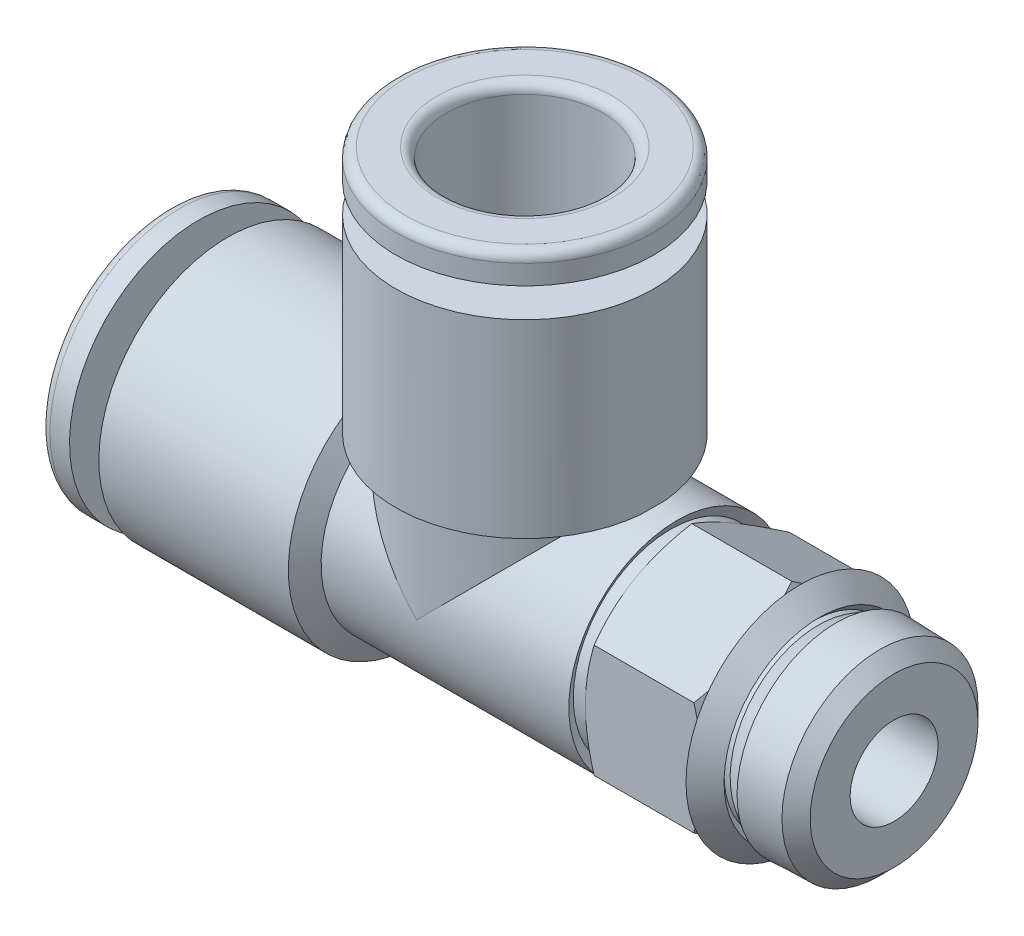
SolidWorks part; units mm, degrees
material "Nylon 101"
ref_plane "Front Plane" through (0, 0, 0) normal (0, 0, 1) x (1, 0, 0)
ref_plane "Top Plane" through (0, 0, 0) normal (0, 1, 0) x (1, 0, 0)
ref_plane "Right Plane" through (0, 0, 0) normal (1, 0, 0) x (0, 0, -1)
sketch "Sketch0" plane through (0, 0, 0) normal (0, 0, -1) x (-1, 0, 0)
  line L0 (0, 0) -> (-37.1, 0) construction
  line L1 (0, 6.6) -> (0, -6.6) construction
  line L2 (-14.2, 4) -> (-14.2, -4) construction
  line L3 (-32.3, 5.1435) -> (-32.3, -5.1435) construction
  line L4 (-18.55, 5) -> (-18.55, -5) construction
  line L5 (-37.1, 2.25) -> (-37.1, -2.25) construction
  line L6 (-18.2, 18.2) -> (-18.2, 0) construction
  line L7 (-32.3, 5) -> (-32.3, -5) construction
  line L8 (-18.2, 18.2) -> (-18.2, 4.001) construction
  point P3 (-14.2, 0)
  point P11 (-18.55, 0)
  point P16 (-32.3, 0)
  dimension "D3" = 14.199
sketch "Sketch1" plane through (0, 0, 0) normal (0, 0, -1) x (-1, 0, 0)
  line L0 (0, 6.1) -> (0, 4.5)
  line L1 (-0.5, 6.6) -> (-1.5, 6.6)
  line L2 (-1.5, 6.6) -> (-1.5, 4.475)
  line L3 (-1.5, 4.475) -> (-3, 4.475)
  line L4 (-3, 4.475) -> (-3, 6.6)
  line L5 (-3, 6.6) -> (-12.6989, 6.6)
  line L6 (-13.3123, 5.5375) -> (-18.2, 5.5375)
  line L7 (0, 0) -> (-37.1, 0) construction
  line L8 (-18.2, 0) -> (-14.2, 0)
  line L9 (-14.2, 4) -> (-14.2, 0)
  line L10 (0, 0) -> (-37.1, 0) construction
  line L11 (-14.2, 4) -> (-0.5, 4)
  line L12 (0, 6.6) -> (0, -6.6) construction
  line L13 (-18.2, 18.2) -> (-18.2, 0) construction
  line L15 (-18.2, 5.5375) -> (-18.2, 0)
  line L16 (-12.6989, 6.6) -> (-13.3123, 5.5375)
  line L17 (-13.3123, 5.5375) -> (-14.2, 4) construction
  line L18 (-3, 5.5375) -> (-13.3123, 5.5375) construction
  arc A0 (0, 6.1) -> (-0.5, 6.6) centre (-0.5, 6.1) ccw
  arc A1 (-0.5, 4) -> (0, 4.5) centre (-0.5, 4.5) ccw
  point P15 (0, 6.6)
  point P19 (0, 6.6)
  point P25 (0, 4)
  dimension "D4" = 60
  dimension "R" = 0.5
  dimension "D1" = 1.5
  dimension "D3" = 8.95
  dimension "D2" = 1.5
revolve "Revolve1" add sketch "Sketch1" angle 360 about L10
sketch "Sketch1.5" plane through (0, 0, 0) normal (0, 0, 1) x (1, 0, 0)
  line L0 (18.2, 0) -> (18.2, 18.2) construction
  line L1 (22.7, 18.2) -> (24.3, 18.2)
  line L2 (24.8, 17.7) -> (24.8, 16.7)
  line L3 (24.8, 16.7) -> (22.675, 16.7)
  line L4 (22.675, 16.7) -> (22.675, 15.2)
  line L5 (22.675, 15.2) -> (24.8, 15.2)
  line L6 (24.8, 15.2) -> (24.8, 5.5011)
  line L7 (24.8, 5.5011) -> (23.7375, 4.8877)
  line L8 (23.7375, 4.8877) -> (23.7375, 0)
  line L9 (0, 0) -> (37.1, 0) construction
  line L10 (23.7375, 0) -> (18.2, 0)
  line L11 (18.2, 0) -> (18.2, 4)
  line L12 (18.2, 4) -> (22.2, 4)
  line L13 (22.2, 4) -> (22.2, 17.7)
  line L14 (1.5, 4.475) -> (3, 4.475) construction
  line L16 (0, 6.1) -> (0, 4.5) construction
  line L17 (14.2, 4) -> (0.5, 4) construction
  line L18 (14.2, 4) -> (14.2, 0) construction
  line L19 (1.5, 6.6) -> (1.5, 4.475) construction
  line L20 (0.5, 6.6) -> (1.5, 6.6) construction
  line L21 (3, 6.6) -> (12.6989, 6.6) construction
  line L22 (18.2, 5.5375) -> (18.2, 0) construction
  line L23 (12.6989, 6.6) -> (13.3123, 5.5375) construction
  arc A0 (24.3, 18.2) -> (24.8, 17.7) centre (24.3, 17.7) cw
  arc A1 (22.7, 18.2) -> (22.2, 17.7) centre (22.7, 17.7) ccw
  arc A2 (0.5, 6.6) -> (0, 6.1) centre (0.5, 6.1) ccw construction
revolve "Revolve2" add sketch "Sketch1.5" angle 360 about L0
ref_plane "Plane1" through (32.3, 0, 0) normal (1, 0, 0) x (0, 0, -1)
sketch "Sketch2" plane through (32.3, 0, 0) normal (1, 0, 0) x (0, 0, -1)
  circle A0 centre (0, 0) radius 5.1435
  point P5 (0, -5.1435)
extrude "Extrude1" add sketch "Sketch2" along normal up to vertex (4.8 mm away) draft 1.783 separate body up to point (37.1, 0, 0)
sketch "Sketch4" plane through (0, 0, 0) normal (0, 0, -1) x (-1, 0, 0)
  line L0 (-37.9659, 5.094) -> (-37.5041, 4.2941) construction
  line L1 (-37.5041, 4.2941) -> (-37.0423, 5.094) construction
  line L2 (-37.0423, 5.094) -> (-37.9659, 5.094) construction
  line L3 (-37.9082, 4.9941) -> (-37.1, 4.9941) construction
  line L4 (-37.5041, 5.094) -> (-37.5041, 4.9941) construction
  line L5 (-37.5041, 4.9941) -> (-37.5041, 4.3941) construction
  line L6 (-37.5041, 4.3941) -> (-37.5041, 4.2941) construction
  line L7 (-37.5618, 4.3941) -> (-37.4464, 4.3941)
  line L8 (-37.0423, 5.094) -> (-37.9082, 4.9941)
  line L9 (-37.0423, 5.094) -> (-37.4464, 4.3941)
  line L10 (-37.9082, 4.9941) -> (-37.5618, 4.3941)
  line L11 (-37.5041, 4.2941) -> (-37.5041, -4.9815) construction
  line L12 (-37.5041, -4.9815) -> (-36.5809, -5.0102) construction
  line L13 (-36.5809, -5.0102) -> (-35.6577, -5.039) construction
  line L14 (-35.6577, -5.039) -> (-34.7345, -5.0677) construction
  line L15 (-34.7345, -5.0677) -> (-33.8113, -5.0964) construction
  line L16 (-37.1, -4.9941) -> (-32.3, -5.1435) construction
  dimension "D1" = 0.9236
  dimension "D2" = 0.1155
sketch "Sketch5" plane through (37.1, 0, 0) normal (1, 0, 0) x (0, 0, -1)
  circle A0 centre (0, 0) radius 4.2941
extrude "Extrude2" cut sketch "Sketch5" against normal up to vertex (4.8 mm away) draft 45 flip side to cut up to point (32.3, 0, 0)
sketch "Sketch6" plane through (0, 0, 0) normal (0, 0, 1) x (1, 0, 0)
  line L0 (32.3, -5.1435) -> (33.2232, -5.1148)
  line L1 (37.5041, -4.9815) -> (36.5809, -5.0102) construction
  line L2 (33.2232, -5.1148) -> (34.1464, -5.086)
  line L3 (34.1464, -5.086) -> (33.2232, -4.5148)
  line L4 (33.2232, -4.5148) -> (33.2232, -5.1148) construction
  line L5 (37.5041, 4.9941) -> (37.5041, 4.3941) construction
  line L6 (33.2232, -4.5148) -> (32.3, -4.5436)
  line L7 (32.3, -4.5436) -> (32.3, -5.1435)
  line L8 (32.3, 0) -> (37.5041, 0) construction
  line L9 (32.3, -5.1435) -> (32.3, 5.1435) construction
  line L10 (37.5041, 4.2941) -> (37.5041, -4.9815) construction
revolve "Cut-Revolve1" cut sketch "Sketch6" angle 360 about L8
sketch "Sketch7" plane through (32.3, 0, 0) normal (-1, 0, 0) x (0, 0, 1)
  circle A2 centre (0, 0) radius 5.1435
  circle A3 centre (0, 0) radius 5.1435
  dimension "D1" = 0
extrude "Extrude3" add sketch "Sketch7" against normal blind 3 draft 45
sketch "Sketch8" plane through (32.3, 0, 0) normal (1, 0, 0) x (0, 0, -1)
  line L1 (0, 5.7735) -> (-5, 2.8868)
  line L2 (-5, 2.8868) -> (-5, -2.8868)
  line L3 (-5, -2.8868) -> (0, -5.7735)
  line L4 (0, -5.7735) -> (5, -2.8868)
  line L5 (5, -2.8868) -> (5, 2.8868)
  line L6 (5, 2.8868) -> (0, 5.7735)
  circle A0 centre (0, 0) radius 5 construction
extrude "Extrude5" add sketch "Sketch8" against normal blind 6
sketch "Sketch9" plane through (32.3, 0, 0) normal (1, 0, 0) x (0, 0, -1)
  circle A0 centre (0, 0) radius 5 construction
  circle A1 centre (0, 0) radius 5
extrude "Extrude6" cut sketch "Sketch9" against normal up to vertex (6 mm away) draft 60 flip side to cut up to point (26.3, 5.7735, 0)
sketch "Sketch10" plane through (26.3, 0, 0) normal (-1, 0, 0) x (0, 0, 1)
  circle A1 centre (0, 0) radius 5
  circle A2 centre (0, 0) radius 5
  dimension "D1" = 0
extrude "Extrude7" cut sketch "Sketch10" against normal up to vertex (6 mm away) draft 60 flip side to cut up to point (32.3, 5.7735, 0)
sketch "Sketch11" plane through (0, 0, 0) normal (0, 0, 1) x (1, 0, 0)
  line L0 (0, 0) -> (37.1, 0) construction
  line L1 (0, 6.1) -> (0, -6.1) construction
  line L3 (32.3, 5.8506) -> (33.2728, 4.8779)
  line L4 (32.9192, 4.5243) -> (33.2728, 4.8779)
  line L5 (32.9192, 4.5243) -> (32.3, 5.1435)
  line L6 (32.3, 5.1435) -> (32.3, 5.8506)
  line L8 (32.9192, 4.5243) -> (32.3, 5.1435) construction
  line L10 (32.9192, -4.5243) -> (32.9192, 4.5243) construction
  dimension "D1" = 0.5
revolve "Revolve3" add sketch "Sketch11" angle 360 about L0
sketch "Sketch12" plane through (0, 0, 0) normal (0, 0, 1) x (1, 0, 0)
  line L0 (18.2, 0) -> (18.2, -5.5375)
  line L2 (18.2, 0) -> (26.3, 0)
  line L3 (26.3, 0) -> (26.3, -5)
  line L4 (26.3, -5) -> (25.6793, -5)
  line L5 (25.6793, -5) -> (25.9897, -5.5375)
  line L6 (25.9897, -5.5375) -> (18.2, -5.5375)
  line L7 (18.2, -5.5375) -> (18.2, 0) construction
  line L8 (13.3123, -5.5375) -> (18.2, -5.5375) construction
  line L9 (32.3, -5) -> (26.3, -5) construction
  dimension "D1" = 60
revolve "Revolve4" add sketch "Sketch12" angle 360 about L2
sketch "Sketch13" plane through (14.2, 0, 0) normal (-1, 0, 0) x (0, 0, 1)
  circle A0 centre (0, 0) radius 4
  arc A1 (-3.8293, 1.1559) -> (3.8293, 1.1559) centre (0, 0) ccw construction
extrude "Extrude8" cut sketch "Sketch13" along normal up to vertex (14.2 mm away) up to point (0, 0, 0)
sketch "Sketch14" plane through (0, 18.2, 0) normal (0, 1, 0) x (1, 0, 0)
  circle A0 centre (18.2, 0) radius 4 construction
  circle A1 centre (18.2, 0) radius 4
extrude "Extrude9" cut sketch "Sketch14" against normal up to vertex
sketch "Sketch15" plane through (37.1, 0, 0) normal (1, 0, 0) x (0, 0, -1)
  circle A0 centre (0, 0) radius 2.25
extrude "Extrude10" cut sketch "Sketch15" against normal up to vertex
sketch "Sketch16" plane through (0, 4.001, 0) normal (0, 1, 0) x (1, 0, 0)
  line L0 (18.2, 2.25) -> (18.2, -2.25) construction
  line L1 (37.1, 2.25) -> (14.2, 2.25) construction
  circle A0 centre (18.2, 0) radius 2.25
  circle A1 centre (18.2, 0) radius 4 construction
extrude "Extrude11" cut sketch "Sketch16" against normal up to vertex up to point (18.2, 0, 0)
equation "\"D2@Sketch4\" = \"D1@Sketch4\" * 1 / 8"
equation "\"D3@Sketch0\" = \"M@Sketch0\" - 0.001"
